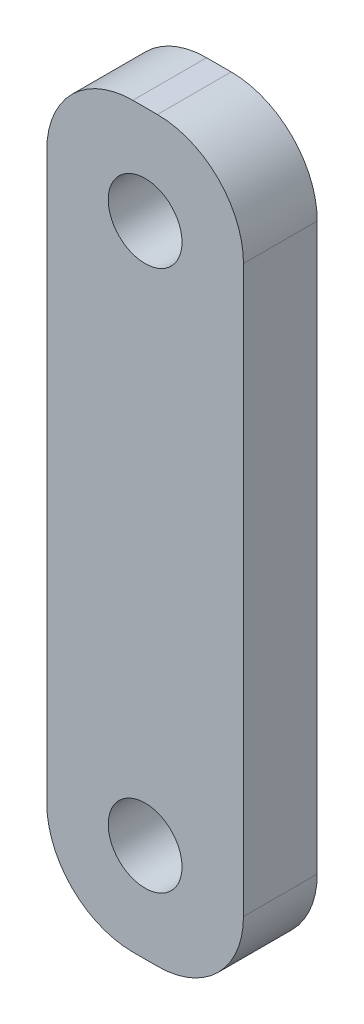
SolidWorks part; units mm, degrees
ref_plane "Front Plane" through (0, 0, 0) normal (1, 0, 0) x (0, 1, 0)
ref_plane "Top Plane" through (0, 0, 0) normal (0, 0, 1) x (0, 1, 0)
ref_plane "Right Plane" through (0, 0, 0) normal (0, 1, 0) x (-1, 0, 0)
sketch "Sketch1" plane through (0, 0, 0) normal (0, 0, 1) x (0, 1, 0)
  line L1 (-15, 4) -> (15, 4)
  line L2 (-15, 4) -> (-15, -4)
  line L3 (-15, -4) -> (15, -4)
  line L4 (15, 4) -> (15, -4)
  line L5 (-15, 4) -> (15, -4) construction
  line L6 (-15, -4) -> (15, 4) construction
  point P0 (0, 0)
  dimension "D1" = 30
  dimension "D2" = 8
extrude "Boss-Extrude1" add sketch "Sketch1" against normal blind 3
sketch "Sketch2" plane through (0, 0, 0) normal (0, 0, 1) x (1, 0, 0)
  line L0 (-4, -15) -> (4, -15) construction
  line L1 (4, 15) -> (-4, 15) construction
  circle A0 centre (0, 11) radius 1.5
  circle A1 centre (0, -11) radius 1.5
  dimension "D1" = 3
  dimension "D2" = 3
  dimension "D3" = 4
  dimension "D4" = 4
extrude "Cut-Extrude1" cut sketch "Sketch2" against normal blind 4
fillet "Fillet1" radius 3.5 4 edges at (4, -15, -1.5) (-4, -15, -1.5) (-4, 15, -1.5) (4, 15, -1.5)
scale "Scale1" scale about centroid uniform scaling yes scale factor 0.75
scale "Scale2" scale about centroid uniform scaling yes scale factor 0.7
